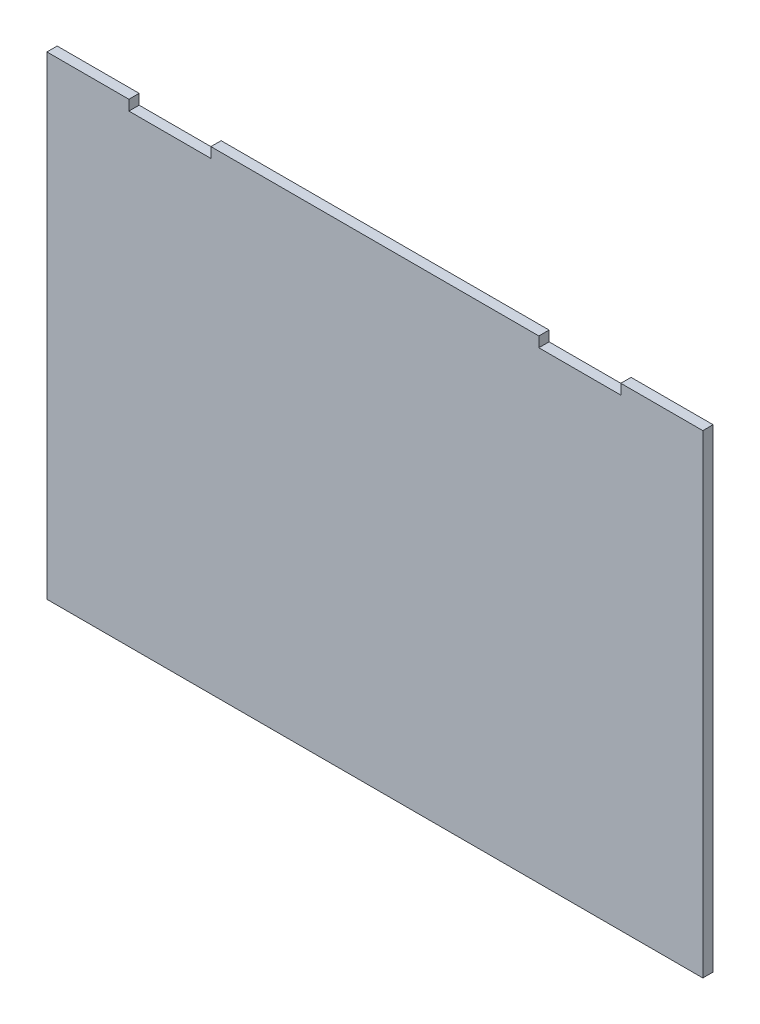
SolidWorks part; units mm, degrees
ref_plane "Front Plane" through (0, 0, 0) normal (0, 0, 1) x (1, 0, 0)
ref_plane "Top Plane" through (0, 0, 0) normal (0, 1, 0) x (1, 0, 0)
ref_plane "Right Plane" through (0, 0, 0) normal (1, 0, 0) x (0, 0, -1)
sketch "Sketch1" plane through (0, 0, 0) normal (0, 0, 1) x (1, 0, 0)
  line L0 (-105.2286, 0) -> (97.9714, 0)
  line L1 (97.9714, 0) -> (97.9714, 146.8628)
  line L2 (97.9714, 146.8628) -> (72.5714, 146.8628)
  line L3 (72.5714, 146.8628) -> (72.5714, 143.6878)
  line L4 (72.5714, 143.6878) -> (47.1714, 143.6878)
  line L5 (47.1714, 143.6878) -> (47.1714, 146.8628)
  line L6 (47.1714, 146.8628) -> (-54.4286, 146.8628)
  line L7 (-54.4286, 146.8628) -> (-54.4286, 143.6878)
  line L8 (-54.4286, 143.6878) -> (-79.8286, 143.6878)
  line L9 (-79.8286, 143.6878) -> (-79.8286, 146.8628)
  line L10 (-79.8286, 146.8628) -> (-105.2286, 146.8628)
  line L11 (-105.2286, 146.8628) -> (-105.2286, 0)
  dimension "D1" = 25.4
  dimension "D2" = 146.8628
  dimension "D3" = 203.2
  dimension "D4" = 3.175
extrude "Boss-Extrude1" add sketch "Sketch1" along normal blind 3.175
